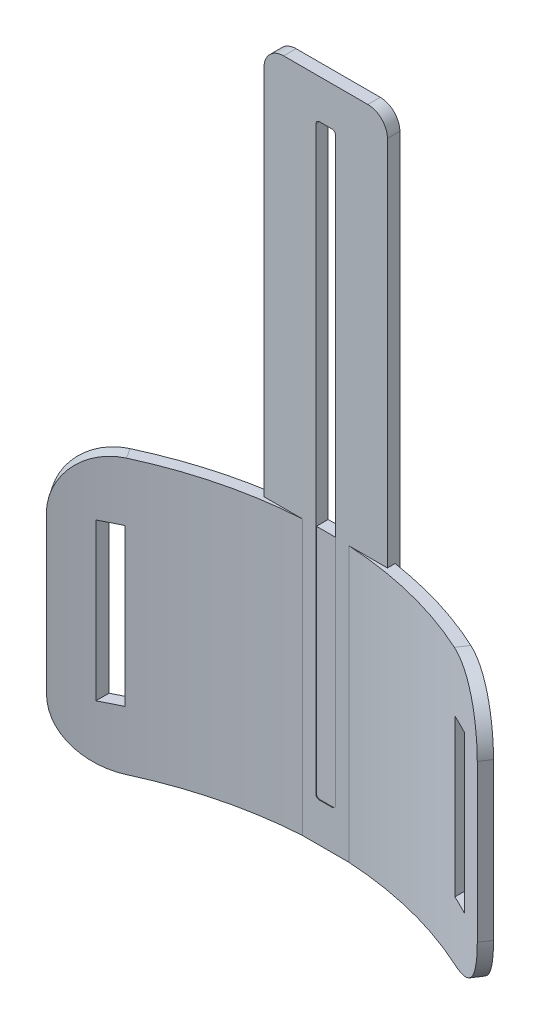
SolidWorks part; units mm, degrees
ref_plane "Front Plane" through (0, 0, 0) normal (0, 0, 1) x (1, 0, 0)
ref_plane "Top Plane" through (0, 0, 0) normal (0, 1, 0) x (1, 0, 0)
ref_plane "Right Plane" through (0, 0, 0) normal (1, 0, 0) x (0, 0, -1)
sketch "Sketch1" plane through (0, 0, 0) normal (0, 0, 1) x (1, 0, 0)
  line L0 (-15.75, 85) -> (-15.75, -85)
  line L5 (-2.54, -75) -> (2.54, -75)
  line L6 (-2.54, -75) -> (-2.54, 75)
  line L8 (2.54, -75) -> (2.54, 75)
  line L9 (-2.54, -75) -> (2.54, 75) construction
  line L10 (-2.54, 75) -> (2.54, -75) construction
  line L16 (-15.75, -85) -> (15.75, -85)
  line L17 (15.75, -85) -> (15.75, 85)
  line L18 (0, 75) -> (0, -85) construction
  line L25 (-2.54, 75) -> (2.54, 75) construction
  line L28 (-15.75, 85) -> (15.75, 85)
  line L30 (-2.54, 75) -> (2.54, 75)
  point P5 (0, 0)
  dimension "D1" = 31.5
  dimension "D2" = 10
  dimension "D3" = 5.08
  dimension "D4" = 150
  dimension "D8" = 10
extrude "Boss-Extrude1" add sketch "Sketch1" along normal blind 3.175
fillet "Fillet1" radius 1 4 edges at (2.54, -75, 1.5875) (-2.54, -75, 1.5875) (2.54, 75, 1.5875) (-2.54, 75, 1.5875)
fillet "Fillet2" radius 5 4 edges at (15.75, -85, 1.5875) (-15.75, -85, 1.5875) (15.75, 85, 1.5875) (-15.75, 85, 1.5875)
sketch "Sketch3" plane through (0, -85, 0) normal (0, 1, 0) x (1, 0, 0)
  line L0 (0, 0) -> (0, -103) construction
  line L1 (-56.65, -16.978) -> (-55, -19.4835)
  line L2 (56.65, -16.978) -> (55, -19.4835)
  arc A0 (-55, -19.4835) -> (55, -19.4835) centre (0, -103) cw
  arc A1 (-56.65, -16.978) -> (56.65, -16.978) centre (0, -103) cw
  point P5 (0, 0)
  dimension "D2" = 100
  dimension "D3" = 110
  dimension "D1" = 3
extrude "Boss-Extrude2" add sketch "Sketch3" along normal blind 70
fillet "Fillet3" radius 15 4 edges at (55.825, -15, 18.2308) (55.825, -85, 18.2308) (-55.825, -85, 18.2308) (-55.825, -15, 18.2308)
sketch "Sketch4" plane through (0, 0, 0) normal (0, 0, 1) x (1, 0, 0)
  line L0 (-56.65, -50) -> (56.65, -50) construction
  line L1 (-56.65, -30) -> (-56.65, -70) construction
  line L2 (56.65, -30) -> (56.65, -70) construction
  line L3 (0, 0) -> (0, -85) construction
  line L4 (-47.0946, -70) -> (-42.0946, -70)
  line L5 (-47.0946, -70) -> (-47.0946, -30)
  line L6 (-47.0946, -30) -> (-42.0946, -30)
  line L7 (-42.0946, -70) -> (-42.0946, -30)
  line L8 (-47.0946, -70) -> (-42.0946, -30) construction
  line L9 (-47.0946, -30) -> (-42.0946, -70) construction
  line L10 (-5.9135, -85) -> (5.9135, -85) construction
  point P6 (-44.5946, -50)
  dimension "D1" = 40
  dimension "D2" = 5
extrude "Cut-Extrude5" cut sketch "Sketch4" against normal through all and the other way through all
mirror "Mirror1" about plane through (0, 0, 0) normal (1, 0, 0) of "Cut-Extrude5"
